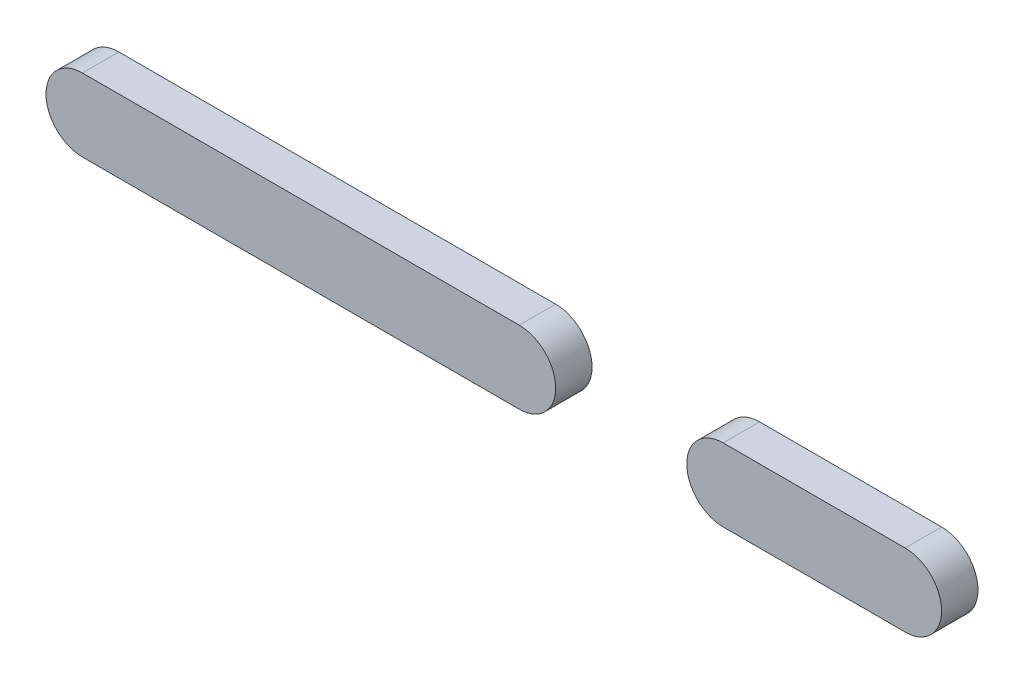
SolidWorks part; units mm, degrees
ref_plane "前视基准面" through (0, 0, 0) normal (0, 0, 1) x (1, 0, 0)
ref_plane "上视基准面" through (0, 0, 0) normal (0, 1, 0) x (1, 0, 0)
ref_plane "右视基准面" through (0, 0, 0) normal (1, 0, 0) x (0, 0, -1)
other "Configuration Table"
sketch "草图1" plane through (0, 0, 0) normal (0, 0, 1) x (1, 0, 0)
  line L0 (-16.5685, -1.5868) -> (-4.5685, -1.5868) construction
  line L1 (-16.5685, -0.5868) -> (-4.5685, -0.5868)
  line L2 (-16.5685, -2.5868) -> (-4.5685, -2.5868)
  line L3 (1.033, -1.5868) -> (6.033, -1.5868) construction
  line L4 (1.033, -0.5868) -> (6.033, -0.5868)
  line L5 (1.033, -2.5868) -> (6.033, -2.5868)
  arc A0 (-16.5685, -0.5868) -> (-16.5685, -2.5868) centre (-16.5685, -1.5868) ccw
  arc A1 (-4.5685, -2.5868) -> (-4.5685, -0.5868) centre (-4.5685, -1.5868) ccw
  arc A2 (1.033, -0.5868) -> (1.033, -2.5868) centre (1.033, -1.5868) ccw
  arc A3 (6.033, -2.5868) -> (6.033, -0.5868) centre (6.033, -1.5868) ccw
  point P2 (-10.5685, -1.5868)
  point P8 (3.533, -1.5868)
  point P14 (-1.0051, 1.228)
  point P15 (-14.5279, 5.1569)
  point P16 (-9.9898, 0.2838)
  point P17 (0, 0)
  point P18 (-12.1827, -1.4522)
  point P19 (-10.5685, -1.0868)
  dimension "D3" = 5
  dimension "D1" = 12
  dimension "D2" = 2
extrude "凸台-拉伸1" add sketch "草图1" along normal blind 1
